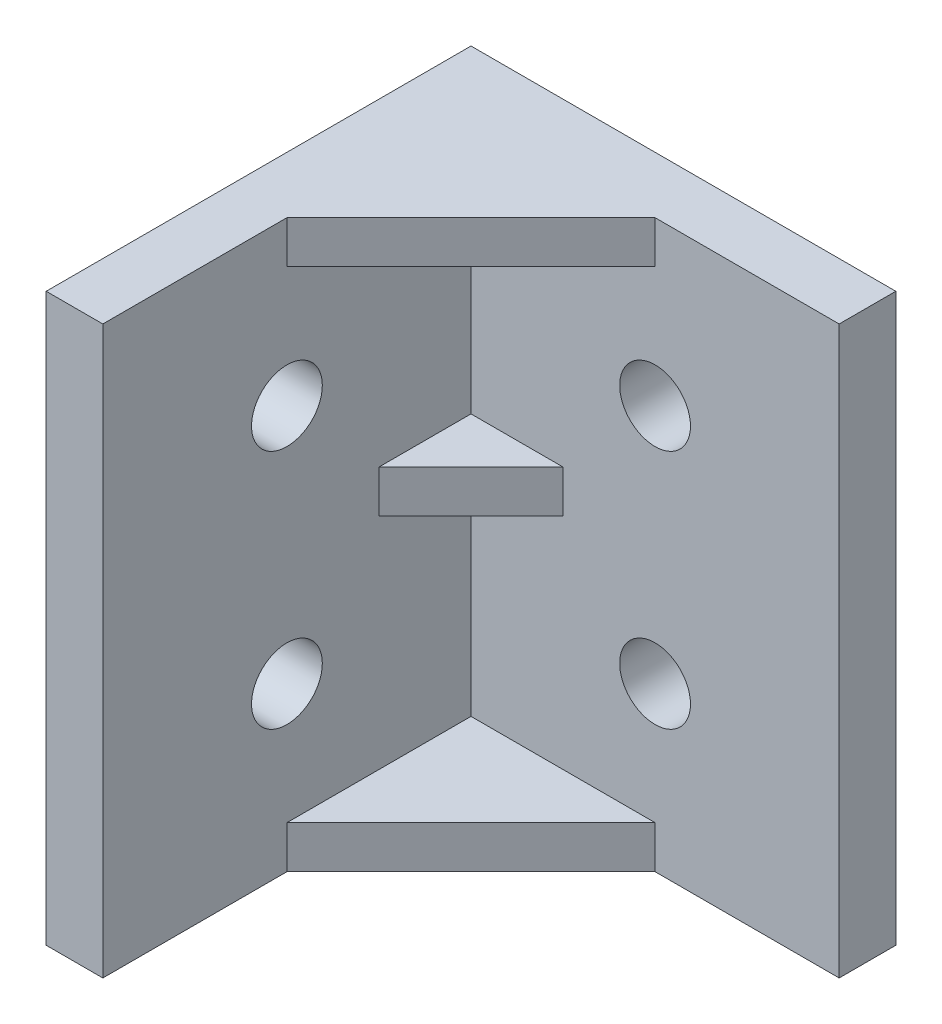
SolidWorks part; units mm, degrees
ref_plane "Alzado" through (0, 0, 0) normal (0, 0, 1) x (1, 0, 0)
ref_plane "Planta" through (0, 0, 0) normal (0, 1, 0) x (1, 0, 0)
ref_plane "Vista lateral" through (0, 0, 0) normal (1, 0, 0) x (0, 0, -1)
sketch "Croquis1" plane through (0, 0, 0) normal (0, 1, 0) x (1, 0, 0)
  line L0 (-19.5152, 8.3738) -> (6.4848, 8.3738)
  line L1 (-23.5152, 12.3738) -> (6.4848, 12.3738)
  line L2 (-23.5152, 12.3738) -> (-23.5152, -17.6262)
  line L3 (-23.5152, -17.6262) -> (-19.5152, -17.6262)
  line L4 (6.4848, 12.3738) -> (6.4848, 8.3738)
  line L5 (-19.5152, 8.3738) -> (-19.5152, -13.6262) construction
  line L6 (-19.5152, 8.3738) -> (2.4848, 8.3738) construction
  line L7 (-19.5152, 8.3738) -> (-19.5152, -17.6262)
  line L8 (-19.5152, -13.6262) -> (2.4848, -13.6262) construction
  line L9 (2.4848, 8.3738) -> (2.4848, -13.6262) construction
  line L10 (-23.5152, -17.6262) -> (6.4848, -17.6262) construction
  line L11 (6.4848, 12.3738) -> (6.4848, -17.6262) construction
  dimension "D1" = 30
  dimension "D2" = 30
  dimension "D3" = 4
extrude "Saliente-Extruir1" add sketch "Croquis1" along normal mid plane 40
sketch "Croquis2" plane through (0, -20, 0) normal (0, -1, 0) x (1, 0, 0)
  line L0 (-6.5152, -8.3738) -> (-19.5152, -8.3738)
  line L1 (-19.5152, -8.3738) -> (6.4848, -8.3738) construction
  line L2 (-19.5152, -8.3738) -> (-19.5152, 4.6262)
  line L3 (-19.5152, 17.6262) -> (-19.5152, -8.3738) construction
  line L4 (-19.5152, 4.6262) -> (-6.5152, -8.3738)
extrude "Saliente-Extruir2" add sketch "Croquis2" against normal blind 3
sketch "Croquis3" plane through (0, 20, 0) normal (0, 1, 0) x (1, 0, 0)
  line L0 (-6.5152, 8.3738) -> (-19.5152, -4.6262)
  line L1 (-19.5152, 8.3738) -> (6.4848, 8.3738) construction
  line L2 (-19.5152, -17.6262) -> (-19.5152, 8.3738) construction
  line L3 (-19.5152, -4.6262) -> (-19.5152, 8.3738)
  line L4 (-19.5152, 8.3738) -> (-6.5152, 8.3738)
extrude "Saliente-Extruir3" add sketch "Croquis3" against normal blind 3
sketch "Croquis4" plane through (0, 0, 0) normal (0, 1, 0) x (1, 0, 0)
  line L0 (-19.5152, 1.8738) -> (-19.5152, 8.3738) construction
  line L1 (-19.5152, 8.3738) -> (-13.0152, 8.3738) construction
  line L2 (-13.0152, 8.3738) -> (-19.5152, 1.8738)
  line L3 (-19.5152, 1.8738) -> (-19.5152, 8.3738)
  line L4 (-19.5152, 8.3738) -> (-13.0152, 8.3738)
  point P7 (-13.1037, 8.3738)
extrude "Saliente-Extruir4" add sketch "Croquis4" along normal mid plane 3
sketch "Croquis5" plane through (-19.5152, 0, 0) normal (1, 0, 0) x (0, 0, -1)
  line L0 (-4.6262, -17) -> (-4.6262, 0) construction
  line L1 (-4.6262, 17) -> (-4.6262, 0) construction
  line L2 (-4.6262, 0) -> (-4.6262, -17) construction
  line L3 (-4.6262, 17) -> (8.3738, 17) construction
  circle A0 centre (-4.6262, -8.5) radius 2.5
  circle A1 centre (-4.6262, 8.5) radius 2.5
  dimension "D1" = 5
  dimension "D2" = 5
extrude "Cortar-Extruir1" cut sketch "Croquis5" against normal through all
sketch "Croquis6" plane through (0, 0, -8.3738) normal (0, 0, 1) x (1, 0, 0)
  line L0 (-6.5152, -17) -> (-6.5152, 17) construction
  line L1 (-6.5152, 17) -> (-6.5152, 0) construction
  line L2 (-6.5152, 0) -> (-6.5152, -17) construction
  line L3 (-6.5152, 0) -> (-6.5152, 17) construction
  circle A0 centre (-6.5152, -8.5) radius 2.5
  circle A1 centre (-6.5152, 8.5) radius 2.5
  dimension "D1" = 5
  dimension "D2" = 5
extrude "Cortar-Extruir2" cut sketch "Croquis6" against normal through all
